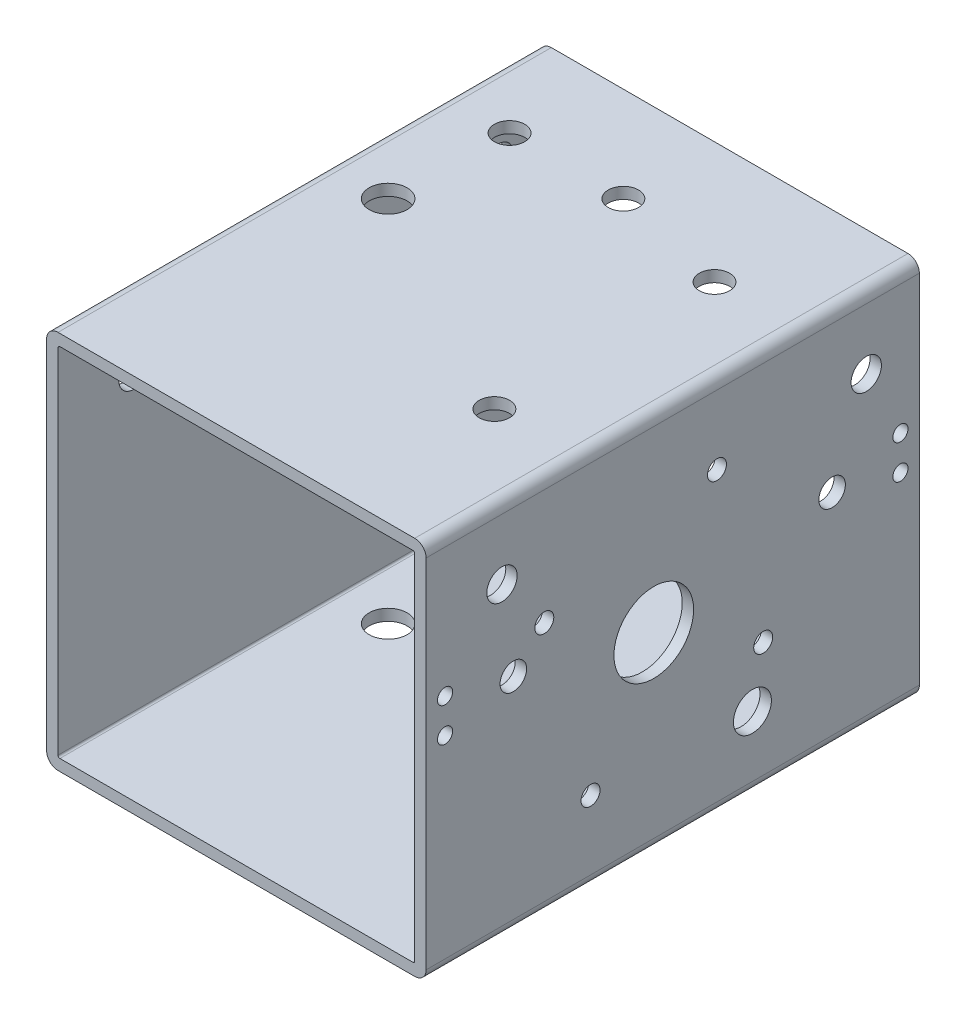
SolidWorks part; units mm, degrees
ref_plane "Front Plane" through (0, 0, 0) normal (0, 0, 1) x (1, 0, 0)
ref_plane "Top Plane" through (0, 0, 0) normal (0, 1, 0) x (1, 0, 0)
ref_plane "Right Plane" through (0, 0, 0) normal (1, 0, 0) x (0, 0, -1)
sketch "Sketch1" plane through (0, 0, 0) normal (0, 0, 1) x (1, 0, 0)
  line L1 (-50, 50) -> (50, 50)
  line L2 (-50, 50) -> (-50, -50)
  line L3 (-50, -50) -> (50, -50)
  line L4 (50, 50) -> (50, -50)
  line L5 (-50, 50) -> (50, -50) construction
  line L6 (-50, -50) -> (50, 50) construction
  point P0 (0, 0)
  dimension "D1" = 100
  dimension "D2" = 100
extrude "Extrude-Thin1" add sketch "Sketch1" along normal blind 130 thin
fillet "Fillet1" radius 0.5 4 edges at (-47, -47, 65) (-47, 47, 65) (47, 47, 65) (47, -47, 65)
fillet "Fillet2" radius 3 4 edges at (50, -50, 65) (-50, -50, 65) (50, 50, 65) (-50, 50, 65)
sketch "Holes - top" plane through (0, 0, 0) normal (0, 1, 0) x (1, 0, 0)
  line L0 (-3, 0) -> (-3, -130) construction
  line L1 (47, -130) -> (-47, -130) construction
  line L2 (-23, 0) -> (-23, -130) construction
  line L3 (47, 0) -> (-47, 0) construction
  line L4 (17, 0) -> (17, -130) construction
  circle A0 centre (-34, -56) radius 11 construction
  circle A1 centre (28, -90) radius 11 construction
  circle A2 centre (28, -32) radius 11 construction
  dimension "D4" = 22
  dimension "D1" = 40
  dimension "D2" = 40
  dimension "D3" = 32
  dimension "D5" = 56
  dimension "D6" = 3
hole_wizard "Ø8.0 (8) Diameter Hole2" positions "Sketch6" profile "Sketch5" hole size "Ø8.0" standard "ANSI Metric" end condition through all
sketch "Sketch6" plane through (0, 50, 0) normal (0, 1, 0) x (1, 0, 0)
  point P0 (28, -32)
  point P6 (28, -90)
sketch "Sketch5" plane through (28, 50, 32) normal (1, 0, 0) x (0, 0, 1)
  line L0 (0, 0) -> (0, 100)
  line L1 (0, 100) -> (4, 100)
  line L2 (4, 100) -> (4, 0)
  line L5 (4, 0) -> (0, 0)
  line L11 (0, -6.35) -> (0, 107.95) construction
  dimension "Thru Hole Dia." = 8
  dimension "Thru Hole Depth" = 100
sketch "Holes - side" plane through (0, 0, 0) normal (1, 0, 0) x (0, 0, -1)
  line L0 (0, 0) -> (-130, 0) construction
  line L1 (-130, -47) -> (-130, 47) construction
  line L2 (-130, 20) -> (0, 20) construction
  line L3 (0, -47) -> (0, 47) construction
  line L4 (-130, -20) -> (0, -20) construction
  circle A0 centre (-110, 31) radius 11 construction
  circle A1 centre (-14, 31) radius 11 construction
  circle A2 centre (-44, -31) radius 11 construction
  dimension "D1" = 40
  dimension "D2" = 22
  dimension "D3" = 20
  dimension "D4" = 14
  dimension "D5" = 44
hole_wizard "Ø8.0 (8) Diameter Hole3" positions "Sketch9" profile "Sketch8" hole size "Ø8.0" standard "ANSI Metric" end condition through all
sketch "Sketch9" plane through (50, 0, 0) normal (1, 0, 0) x (0, 0, -1)
  point P0 (-14, 31)
  point P3 (-110, 31)
sketch "Sketch8" plane through (50, 31, 14) normal (0, 1, 0) x (0, 0, -1)
  line L0 (0, 0) -> (0, 100)
  line L1 (0, 100) -> (4, 100)
  line L2 (4, 100) -> (4, 0)
  line L5 (4, 0) -> (0, 0)
  line L11 (0, -6.35) -> (0, 107.95) construction
  dimension "Thru Hole Dia." = 8
  dimension "Thru Hole Depth" = 100
hole_wizard "Ø10.0 (10) Diameter Hole1" positions "Sketch12" profile "Sketch11" hole size "Ø10.0" standard "ANSI Metric" end condition through all
sketch "Sketch12" plane through (0, 50, 0) normal (0, 1, 0) x (1, 0, 0)
  point P0 (-34, -56)
sketch "Sketch11" plane through (-34, 50, 56) normal (1, 0, 0) x (0, 0, 1)
  line L0 (0, 0) -> (0, 100)
  line L1 (0, 100) -> (5, 100)
  line L2 (5, 100) -> (5, 0)
  line L5 (5, 0) -> (0, 0)
  line L11 (0, -6.35) -> (0, 107.95) construction
  dimension "Thru Hole Dia." = 10
  dimension "Thru Hole Depth" = 100
hole_wizard "Ø10.0 (10) Diameter Hole2" positions "Sketch14" profile "Sketch13" hole size "Ø10.0" standard "ANSI Metric" end condition through all
sketch "Sketch14" plane through (50, 0, 0) normal (1, 0, 0) x (0, 0, -1)
  point P0 (-44, -31)
sketch "Sketch13" plane through (50, -31, 44) normal (0, 1, 0) x (0, 0, -1)
  line L0 (0, 0) -> (0, 100)
  line L1 (0, 100) -> (5, 100)
  line L2 (5, 100) -> (5, 0)
  line L5 (5, 0) -> (0, 0)
  line L11 (0, -6.35) -> (0, 107.95) construction
  dimension "Thru Hole Dia." = 10
  dimension "Thru Hole Depth" = 100
hole_wizard "M8x1.25 Tapped Hole1" positions "Sketch18" profile "Sketch17" tap size "M8x1.25" standard "ANSI Metric"
sketch "Sketch18" plane through (-50, 0, 0) normal (-1, 0, 0) x (0, 0, 1)
  line L0 (56, 35) -> (56, -15) construction
  point P0 (56, -15)
  point P2 (56, 35)
  dimension "D1" = 56
  dimension "D2" = 35
  dimension "D3" = 15
sketch "Sketch17" plane through (-50, -15, 56) normal (0, 1, 0) x (0, 0, 1)
  line L0 (0, 0) -> (0, 3)
  line L1 (0, 3) -> (3.4, 3)
  line L2 (3.4, 3) -> (3.4, 0)
  line L5 (3.4, 0) -> (0, 0)
  line L11 (0, -6.35) -> (0, 107.95) construction
  dimension "Thru Tap Drill Dia." = 6.8
  dimension "Thru Tap Drill Depth" = 3
cosmetic thread "Hole Thread1" parameters "D2"=8
cosmetic thread "Hole Thread2" parameters "D2"=8
hole_wizard "M8x1.25 Tapped Hole2" positions "Sketch21" profile "Sketch20" tap size "M8x1.25" standard "ANSI Metric"
sketch "Sketch21" plane through (0, -50, 0) normal (0, -1, 0) x (-1, 0, 0)
  line L0 (20, -44) -> (-35, -44) construction
  point P0 (20, -44)
  point P2 (-35, -44)
  dimension "D1" = 44
  dimension "D2" = 35
  dimension "D3" = 20
sketch "Sketch20" plane through (-20, -50, 44) normal (1, 0, 0) x (0, 0, -1)
  line L0 (0, 0) -> (0, 3)
  line L1 (0, 3) -> (3.4, 3)
  line L2 (3.4, 3) -> (3.4, 0)
  line L5 (3.4, 0) -> (0, 0)
  line L11 (0, -6.35) -> (0, 107.95) construction
  dimension "Thru Tap Drill Dia." = 6.8
  dimension "Thru Tap Drill Depth" = 3
cosmetic thread "Hole Thread3" parameters "D2"=8
cosmetic thread "Hole Thread4" parameters "D2"=8
sketch "Holes - Nema 23 motor" plane through (0, 0, 0) normal (1, 0, 0) x (0, 0, -1)
  line L0 (-98.8427, 16.6524) -> (-53.3476, 28.8427) construction
  line L1 (-98.8427, 16.6524) -> (-86.6524, -28.8427) construction
  line L2 (-53.3476, 28.8427) -> (-41.1573, -16.6524) construction
  line L3 (-86.6524, -28.8427) -> (-41.1573, -16.6524) construction
  line L4 (-98.8427, 16.6524) -> (-41.1573, -16.6524) construction
  line L5 (-53.3476, 28.8427) -> (-86.6524, -28.8427) construction
  line L6 (0, 0) -> (-130, 0) construction
  point P1 (-70, 0)
  dimension "D1" = 70
  dimension "D2" = 47.1
  dimension "D3" = 47.1
  dimension "D4" = 15
hole_wizard "Ø21.0 (21) Diameter Hole1" positions "Sketch24" profile "Sketch23" hole size "Ø21.0" standard "ANSI Metric"
sketch "Sketch24" plane through (50, 0, 0) normal (1, 0, 0) x (0, 0, -1)
  point P0 (-70, 0)
sketch "Sketch23" plane through (50, 0, 70) normal (0, 1, 0) x (0, 0, -1)
  line L0 (0, 0) -> (0, 3)
  line L1 (0, 3) -> (10.5, 3)
  line L2 (10.5, 3) -> (10.5, 0)
  line L5 (10.5, 0) -> (0, 0)
  line L11 (0, -6.35) -> (0, 107.95) construction
  dimension "Thru Hole Dia." = 21
  dimension "Thru Hole Depth" = 3
hole_wizard "Ø5.0 (5) Diameter Hole1" positions "Sketch26" profile "Sketch25" hole size "Ø5.0" standard "ANSI Metric"
sketch "Sketch26" plane through (50, 0, 0) normal (1, 0, 0) x (0, 0, -1)
  point P0 (-41.1573, -16.6524)
  point P3 (-53.3476, 28.8427)
  point P6 (-98.8427, 16.6524)
  point P9 (-86.6524, -28.8427)
sketch "Sketch25" plane through (50, -16.6524, 41.1573) normal (0, 1, 0) x (0, 0, -1)
  line L0 (0, 0) -> (0, 3)
  line L1 (0, 3) -> (2.5, 3)
  line L2 (2.5, 3) -> (2.5, 0)
  line L5 (2.5, 0) -> (0, 0)
  line L11 (0, -6.35) -> (0, 107.95) construction
  dimension "Thru Hole Dia." = 5
  dimension "Thru Hole Depth" = 3
hole_wizard "Ø8.0 (8) Diameter Hole4" positions "Sketch29" profile "Sketch28" hole size "Ø8.0" standard "ANSI Metric"
sketch "Sketch29" plane through (0, 50, 0) normal (0, 1, 0) x (1, 0, 0)
  line L0 (-3, 0) -> (-3, -130) construction
  point P0 (-3, -25)
  dimension "D2" = 7
sketch "Sketch28" plane through (-3, 50, 25) normal (1, 0, 0) x (0, 0, 1)
  line L0 (0, 0) -> (0, 3)
  line L1 (0, 3) -> (4, 3)
  line L2 (4, 3) -> (4, 0)
  line L5 (4, 0) -> (0, 0)
  line L11 (0, -6.35) -> (0, 107.95) construction
  dimension "Thru Hole Dia." = 8
  dimension "Thru Hole Depth" = 3
sketch "Sketch31" plane through (50, 0, 0) normal (1, 0, 0) x (0, 0, -1)
  line L0 (0, -47) -> (0, 47) construction
  line L1 (-130, 50) -> (0, 50) construction
  line L2 (-65, 117.0212) -> (-65, -118.5233) construction
  line L3 (-130, -47) -> (-130, 47) construction
  circle A0 centre (-5, 4) radius 2
  circle A1 centre (-5, 13) radius 2
  circle A2 centre (-125, 13) radius 2
  circle A3 centre (-125, 4) radius 2
  circle A4 centre (-23, 8.5) radius 3.5
  circle A5 centre (-107, 8.5) radius 3.5
  dimension "D1" = 4
  dimension "D2" = 4
  dimension "D3" = 9
  dimension "D4" = 5
  dimension "D5" = 46
  dimension "D6" = 5
  dimension "D8" = 7
  dimension "D9" = 18
  dimension "D7" = 65
  dimension "D10" = 4.5
extrude "Cut-Extrude1" cut sketch "Sketch31" against normal up to next
hole_wizard "Ø8.0 (8) Diameter Hole5" positions "Sketch32" profile "Sketch33" hole size "Ø8.0" standard "ANSI Metric"
sketch "Sketch32" plane through (0, 50, 0) normal (0, 1, 0) x (1, 0, 0)
  line L1 (47, 0) -> (-47, 0) construction
  circle A0 centre (-3, -25) radius 4 construction
  point P0 (-33, -25)
  dimension "D1" = 30
  dimension "D2" = 25
sketch "Sketch33" plane through (-33, 50, 25) normal (1, 0, 0) x (0, 0, 1)
  line L0 (0, 0) -> (0, 3)
  line L1 (0, 3) -> (4, 3)
  line L2 (4, 3) -> (4, 0)
  line L5 (4, 0) -> (0, 0)
  line L11 (0, -6.35) -> (0, 107.95) construction
  dimension "Thru Hole Dia." = 8
  dimension "Thru Hole Depth" = 3
equation "\"L\"= 130"
equation "\"D1@Extrude-Thin1\"=\"L\""
equation "\"d-bearing\"= 22'diameter of bearing"
equation "\"D4@Holes - top\"=\"d-bearing\""
equation "\"D2@Holes - side\"=\"d-bearing\""
